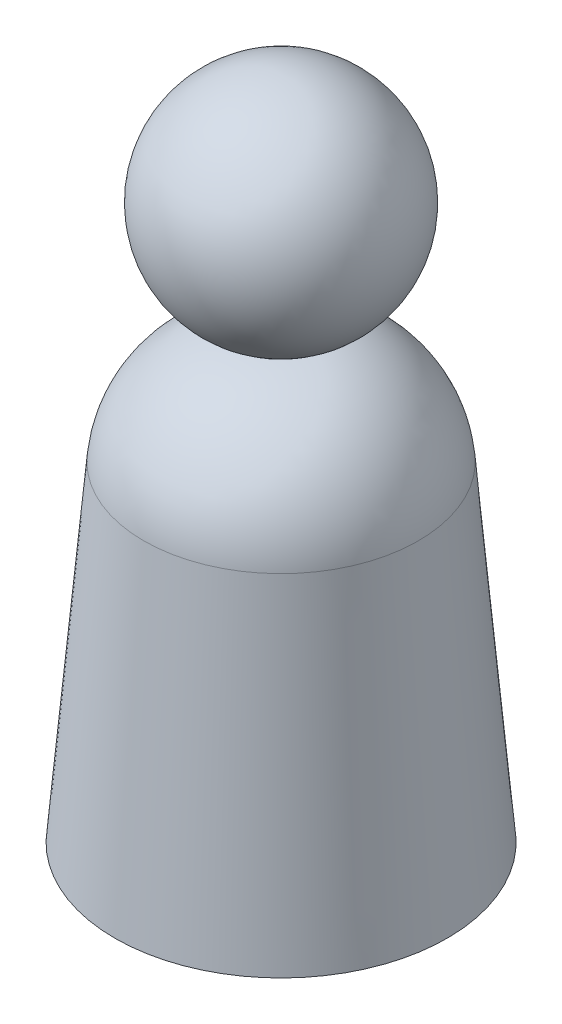
SolidWorks part; units mm, degrees
material "ABS"
ref_plane "Front Plane" through (0, 0, 0) normal (0, 0, 1) x (1, 0, 0)
ref_plane "Top Plane" through (0, 0, 0) normal (0, 1, 0) x (1, 0, 0)
ref_plane "Right Plane" through (0, 0, 0) normal (1, 0, 0) x (0, 0, -1)
sketch "Sketch1" plane through (0, 0, 0) normal (1, 0, 0) x (0, 0, -1)
  line L0 (0, 152.4) -> (0, -152.4)
  circle A0 centre (0, 0) radius 152.4 construction
  arc A1 (0, 152.4) -> (0, -152.4) centre (0, 0) cw
  dimension "D1" = 304.8
revolve "Revolve1" add sketch "Sketch1" angle 360 about L0
sketch "Sketch2" plane through (0, 0, 0) normal (1, 0, 0) x (0, 0, -1)
  line L0 (0, -152.4) -> (0, -762)
  line L1 (0, -762) -> (228.6, -762)
  line L3 (188.9151, -308.4) -> (228.6, -762)
  circle A0 centre (0, 0) radius 152.4 construction
  arc A2 (8.5259, -152.1613) -> (0, -152.4) centre (0, 0) cw
  arc A3 (8.5259, -152.1613) -> (188.9151, -308.4) centre (18.1176, -323.3428) cw
  point P8 (170.9411, -275.7565)
  point P11 (201.076, -286.9806)
  point P12 (0, 0)
  point P13 (216.2503, -306.4937)
  point P14 (0, 0)
  dimension "D3" = 171.45
  dimension "D1" = 609.6
  dimension "D2" = 228.6
  dimension "D4" = 85
revolve "Revolve2" add sketch "Sketch2" angle 360 about L0
